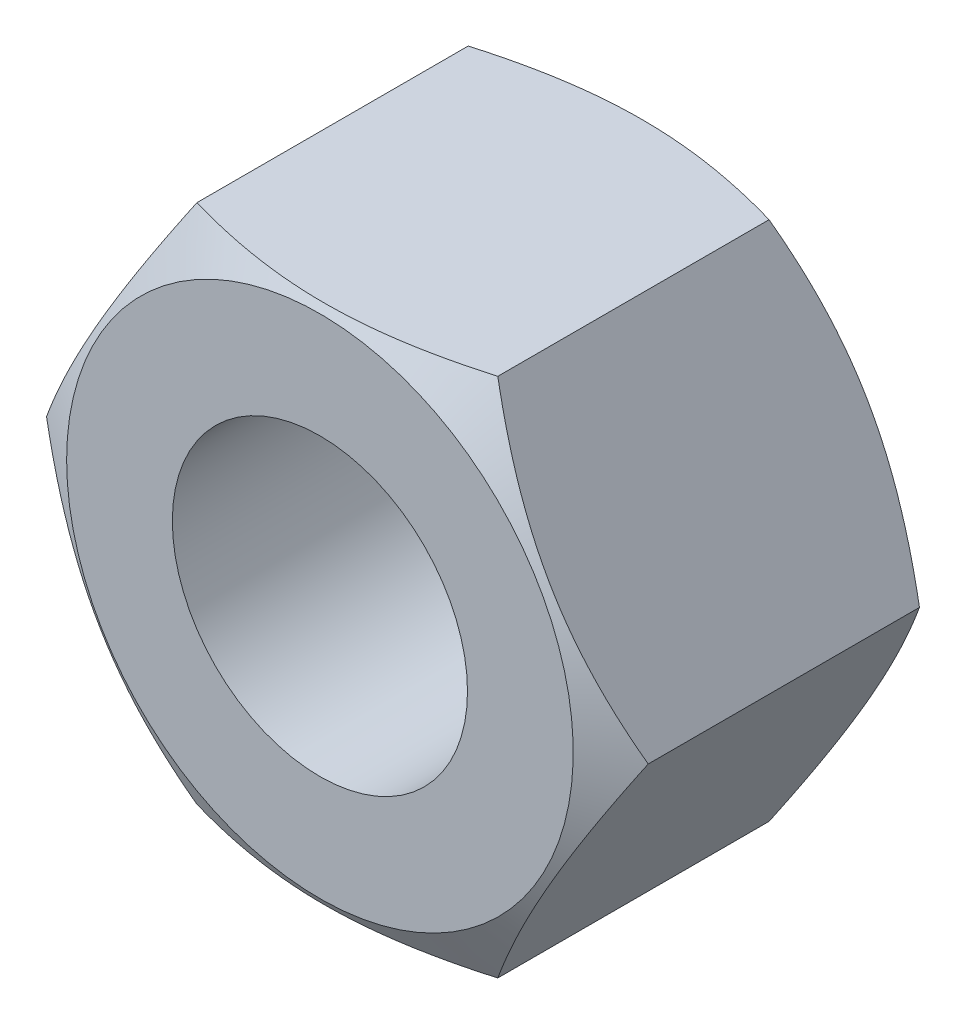
SolidWorks part; units mm, degrees
ref_plane "Front" through (0, 0, 0) normal (0, 0, 1) x (1, 0, 0)
ref_plane "Top" through (0, 0, 0) normal (0, 1, 0) x (1, 0, 0)
ref_plane "Right" through (0, 0, 0) normal (1, 0, 0) x (0, 0, -1)
other "Configuration Table"
sketch "Sketch1" plane through (0, 0, 0) normal (0, 0, 1) x (1, 0, 0)
  line L1 (7.7942, -13.5) -> (15.5885, 0)
  line L2 (15.5885, 0) -> (7.7942, 13.5)
  line L3 (7.7942, 13.5) -> (-7.7942, 13.5)
  line L4 (-7.7942, 13.5) -> (-15.5885, 0)
  line L5 (-15.5885, 0) -> (-7.7942, -13.5)
  line L6 (-7.7942, -13.5) -> (7.7942, -13.5)
  circle A0 centre (0, 0) radius 13.5 construction
  circle A1 centre (0, 0) radius 7.647
  dimension "D" = 15.294
  dimension "s" = 27
extrude "BaseNut" add sketch "Sketch1" against normal blind 16.9
cosmetic thread "ThreadCosmetic1" [suppressed] parameters "D"=18
sketch "Sketch2" plane through (0, 0, 0) normal (0, 1, 0) x (1, 0, 0)
  line L0 (-15.5885, 16.9) -> (-13.125, 16.9)
  line L2 (-13.125, 16.9) -> (-15.5885, 15.4777)
  line L3 (-15.5885, 15.4777) -> (-15.5885, 16.9)
  line L4 (0, 3.3759) -> (0, -9.8171) construction
  line L6 (-9.7712, 8.45) -> (9.8853, 8.45) construction
  line L7 (-15.5885, 1.4223) -> (-15.5885, 0)
  line L8 (-13.125, 0) -> (-15.5885, 1.4223)
  line L9 (-15.5885, 0) -> (-13.125, 0)
  line L10 (-15.5885, 16.9) -> (-15.5885, 0) construction
  dimension "dw" = 26.25
  dimension "D1" = 30
  dimension "D2" = 8.45
revolve "Double-Chamfer" cut sketch "Sketch2" angle 360 about L4
sketch "Sketch4" plane through (0, 0, 0) normal (0, 1, 0) x (1, 0, 0)
  line L0 (8.8187, 16.9) -> (7.647, 16.2235)
  line L1 (7.647, 16.2235) -> (6.294, 16.2235)
  line L2 (6.294, 16.2235) -> (6.294, 17.5765)
  line L3 (6.294, 17.5765) -> (7.647, 17.5765)
  line L4 (7.647, 17.5765) -> (8.8187, 16.9)
  line L5 (0, 0) -> (0, 109.7681) construction
  dimension "D1" = 1.353
  dimension "D2" = 15.294
revolve "Cut-Revolve10" [suppressed] cut sketch "Sketch4" angle 360 about L5
pattern_linear "LPattern10" [suppressed] count 11 spacing 1.6236 along (0, 0, -1)
equation "\"dw@Sketch2\" = \"s@Sketch1\"-0.75"
equation "\"D2@Sketch2\" = \"m@BaseNut\" / 2"
equation "\"D2@Sketch4\"=\"D@Sketch1\""
equation "\"D1@Sketch4\" =  (\"D@ThreadCosmetic1\" - \"D2@Sketch4\"  )  / 2"
equation "\"D3@LPattern10\" = \"D1@Sketch4\" * 1.2"
equation "\"D1@LPattern10\" = \"m@BaseNut\" / \"D3@LPattern10\" + 1"
